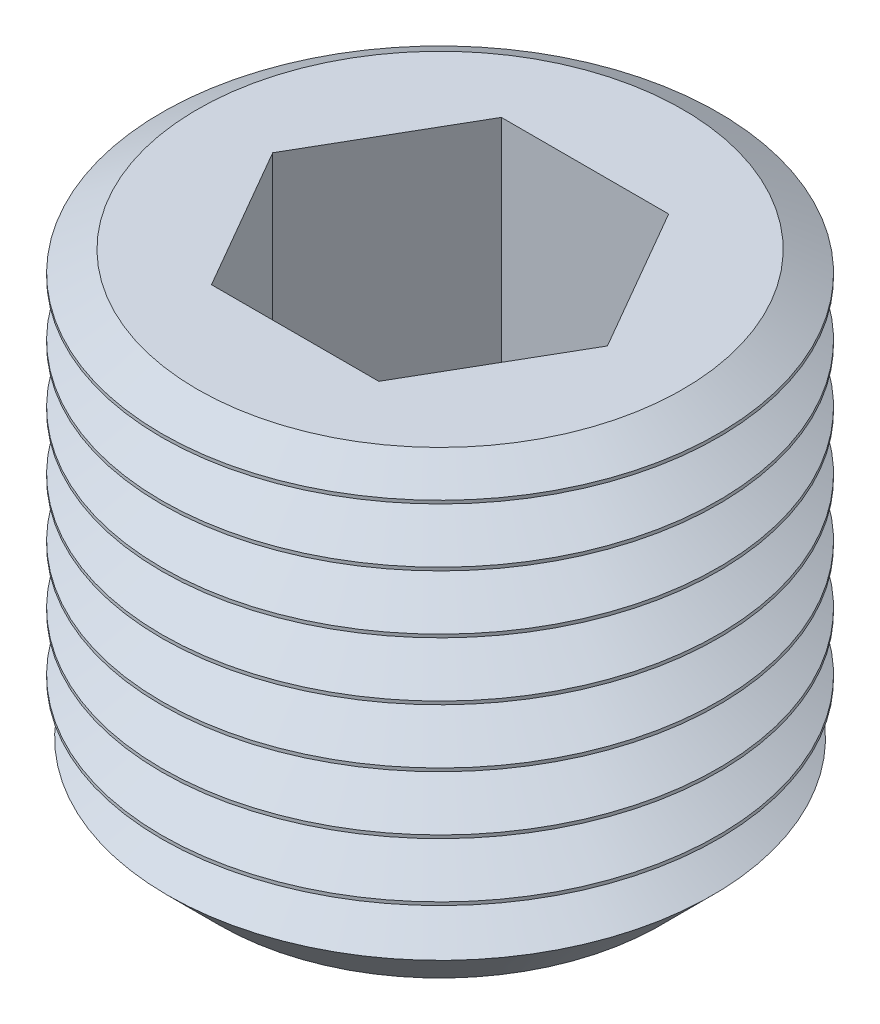
SolidWorks part; units mm, degrees
material "AISI 1045 Steel, cold drawn"
ref_plane "Front Plane" through (0, 0, 0) normal (0, 0, 1) x (1, 0, 0)
ref_plane "Top Plane" through (0, 0, 0) normal (0, 1, 0) x (1, 0, 0)
ref_plane "Right Plane" through (0, 0, 0) normal (1, 0, 0) x (0, 0, -1)
ref_plane "Plane1" through (0, 0, 0) normal (0, 0, -1) x (-1, 0, 0)
sketch "Sketch1" plane through (0, 0, 0) normal (0, 0, -1) x (-1, 0, 0)
  line L0 (-1.9, -4.1) -> (0, -4.1)
  line L1 (0, -4.1) -> (0, 0)
  line L2 (0, 0) -> (-2.0927, 0)
  line L3 (-2.0927, 0) -> (-2.4, -0.1774)
  line L4 (-2.4, -0.1774) -> (-2.4, -0.2051)
  line L5 (-2.4, -0.2051) -> (-1.991, -0.4412)
  line L6 (-1.991, -0.4412) -> (-2.4, -0.6774)
  line L7 (-2.4, -0.6774) -> (-2.4, -0.7051)
  line L8 (-2.4, -0.7051) -> (-1.991, -0.9412)
  line L9 (-1.991, -0.9412) -> (-2.4, -1.1774)
  line L10 (-2.4, -1.1774) -> (-2.4, -1.2051)
  line L11 (-2.4, -1.2051) -> (-1.991, -1.4412)
  line L12 (-1.991, -1.4412) -> (-2.4, -1.6774)
  line L13 (-2.4, -1.6774) -> (-2.4, -1.7051)
  line L14 (-2.4, -1.7051) -> (-1.991, -1.9412)
  line L15 (-1.991, -1.9412) -> (-2.4, -2.1774)
  line L16 (-2.4, -2.1774) -> (-2.4, -2.2051)
  line L17 (-2.4, -2.2051) -> (-1.991, -2.4412)
  line L18 (-1.991, -2.4412) -> (-2.4, -2.6774)
  line L19 (-2.4, -2.6774) -> (-2.4, -2.7051)
  line L20 (-2.4, -2.7051) -> (-1.991, -2.9412)
  line L21 (-1.991, -2.9412) -> (-2.4, -3.1774)
  line L22 (-2.4, -3.1774) -> (-2.4, -3.2051)
  line L23 (-2.4, -3.2051) -> (-1.991, -3.4412)
  line L24 (-1.991, -3.4412) -> (-2.3509, -3.6491)
  line L25 (-2.3509, -3.6491) -> (-1.9, -4.1)
  line L26 (0, -4.1) -> (0, 0) construction
  dimension "D1" = 2.4
  dimension "D2" = 4.1
  dimension "D3" = 2.0927
  dimension "D4" = 0.0277
  dimension "D5" = 0.5
revolve "Revolve1" add sketch "Sketch1" angle 360 about L26
sketch "Sketch2" plane through (0, 0, 0) normal (0, 1, 0) x (-1, 0, 0)
  line L0 (0.7217, -1.25) -> (1.4434, 0)
  line L1 (1.4434, 0) -> (0.7217, 1.25)
  line L2 (0.7217, 1.25) -> (-0.7217, 1.25)
  line L3 (-0.7217, 1.25) -> (-1.4434, 0)
  line L4 (-1.4434, 0) -> (-0.7217, -1.25)
  line L5 (-0.7217, -1.25) -> (0.7217, -1.25)
extrude "Cut-Extrude1" cut sketch "Sketch2" against normal blind 2.5
